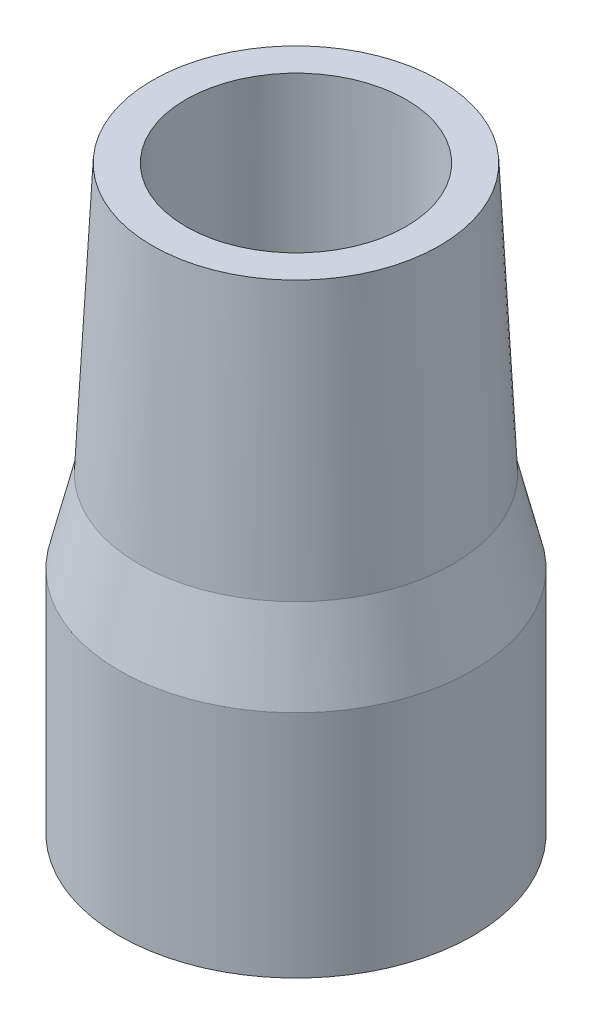
SolidWorks part; units mm, degrees
ref_plane "Front Plane" through (0, 0, 0) normal (0, 0, 1) x (1, 0, 0)
ref_plane "Top Plane" through (0, 0, 0) normal (0, 1, 0) x (1, 0, 0)
ref_plane "Right Plane" through (0, 0, 0) normal (1, 0, 0) x (0, 0, -1)
sketch "Sketch1" plane through (0, 0, 0) normal (0, 0, 1) x (1, 0, 0)
  line L0 (0, 0) -> (0, 3.0295) construction
  line L5 (9.8, 3.2811) -> (10.25, -16.7189)
  line L6 (10.25, -16.7189) -> (13.25, -16.7189)
  line L7 (13.25, -16.7189) -> (13.25, 0.5)
  line L8 (13.25, 0.5) -> (11.75, 6.6466)
  line L9 (11.75, 6.6466) -> (10.75, 26.8086)
  line L10 (10.75, 26.8086) -> (8.25, 26.8086)
  line L11 (8.25, 26.8086) -> (8.2931, 6.8086)
  line L12 (8.2931, 6.8086) -> (8.2931, 3.8086)
  line L13 (8.2931, 3.8086) -> (9.8, 3.8086)
  line L14 (9.8, 3.8086) -> (9.8, 3.2811)
  point P1 (0, 0)
  point P9 (0, 0)
  point P15 (2.8389, 4.7187)
  point P16 (0, 0)
  point P17 (3.8836, 5.7761)
  point P18 (2.8389, 11.1441)
  point P19 (0, 0)
  point P20 (5.2277, 26.2414)
  point P21 (0, 0)
  point P22 (17.9493, 26.6466)
  point P23 (11.629, 6.6466)
  point P24 (8.2931, 26.8086)
  point P25 (13.25, 5.5)
  dimension "D2" = 21.5
  dimension "D3" = 20
  dimension "D4" = 23.5
  dimension "D5" = 2.5
  dimension "D6" = 0.5275
  dimension "D7" = 19.6
  dimension "D8" = 20.5
  dimension "D9" = 20
  dimension "D10" = 3
  dimension "D11" = 3
revolve "Revolve1" add sketch "Sketch1" angle 360 about L0
